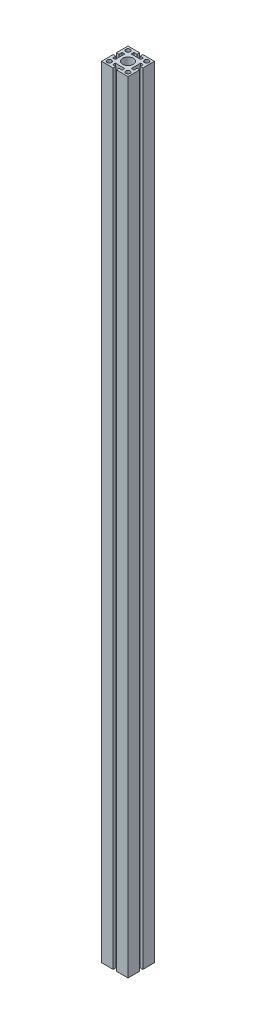
SolidWorks part; units mm, degrees
ref_plane "Front Plane" through (0, 0, 0) normal (0, 0, 1) x (1, 0, 0)
ref_plane "Top Plane" through (0, 0, 0) normal (0, 1, 0) x (1, 0, 0)
ref_plane "Right Plane" through (0, 0, 0) normal (1, 0, 0) x (0, 0, -1)
sketch "Sketch1" plane through (0, 0, 0) normal (0, 1, 0) x (1, 0, 0)
  line L1 (-25, -3) -> (-25, -25)
  line L6 (9, 20) -> (9, 15)
  line L7 (9, 20) -> (3, 20)
  line L8 (9, 15) -> (-9, 15)
  line L9 (3, 20) -> (3, 25)
  line L10 (-3, 25) -> (-25, 25)
  line L11 (-25, 25) -> (-25, 3)
  line L12 (-25, -25) -> (-3, -25)
  line L13 (25, -25) -> (25, -3)
  line L14 (3, 25) -> (25, 25)
  line L15 (-3, 20) -> (-3, 25)
  line L16 (-9, 20) -> (-9, 15)
  line L17 (3, -25) -> (25, -25)
  line L18 (25, 3) -> (25, 25)
  line L19 (-3, 20) -> (-9, 20)
  line L21 (-20, 9) -> (-15, 9)
  line L22 (-20, 9) -> (-20, 3)
  line L24 (-15, 9) -> (-15, -9)
  line L27 (-20, 3) -> (-25, 3)
  line L28 (20, -9) -> (15, -9)
  line L29 (20, -9) -> (20, -3)
  line L30 (15, -9) -> (15, 9)
  line L31 (20, -3) -> (25, -3)
  line L32 (20, 3) -> (25, 3)
  line L33 (-20, -3) -> (-25, -3)
  line L34 (20, 9) -> (15, 9)
  line L35 (20, 3) -> (20, 9)
  line L40 (-20, -9) -> (-15, -9)
  line L41 (-20, -3) -> (-20, -9)
  line L42 (-9, -20) -> (-9, -15)
  line L43 (-9, -20) -> (-3, -20)
  line L44 (-9, -15) -> (9, -15)
  line L45 (-3, -20) -> (-3, -25)
  line L46 (3, -20) -> (3, -25)
  line L47 (9, -20) -> (9, -15)
  line L48 (3, -20) -> (9, -20)
  circle A0 centre (0, 0) radius 10
  circle A1 centre (-17.6777, 17.6777) radius 4.1387
  circle A2 centre (17.6777, 17.6777) radius 4.1387
  circle A3 centre (17.6777, -17.6777) radius 4.1387
  circle A4 centre (-17.6777, -17.6777) radius 4.1387
  point P44 (0, 0)
  point P46 (0, 0)
  dimension "D1" = 4
extrude "Boss-Extrude1" add sketch "Sketch1" along normal blind 1475
